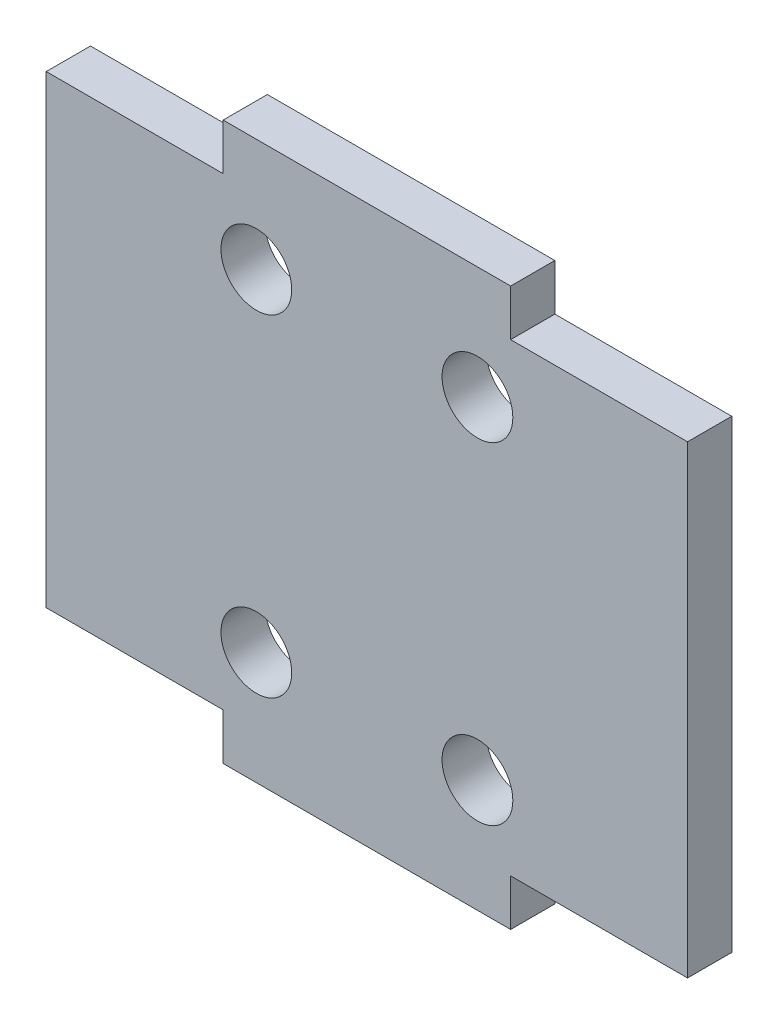
SolidWorks part; units mm, degrees
ref_plane "前视基准面" through (0, 0, 0) normal (0, 0, 1) x (1, 0, 0)
ref_plane "上视基准面" through (0, 0, 0) normal (0, 1, 0) x (1, 0, 0)
ref_plane "右视基准面" through (0, 0, 0) normal (1, 0, 0) x (0, 0, -1)
other "Configuration Table"
sketch "草图1" plane through (0, 0, 0) normal (0, 0, 1) x (1, 0, 0)
  line L0 (0, 0) -> (29, 0)
  line L1 (29, 0) -> (29, 21)
  line L2 (29, 21) -> (0, 21)
  line L3 (0, 21) -> (0, 0)
  line L4 (-8.8099, 10.5) -> (57.9745, 10.5) construction
  line L5 (14.5, 26.0654) -> (14.5, -5.792) construction
  line L6 (8, 0) -> (8, -2.1)
  line L7 (8, -2.1) -> (21, -2.1)
  line L8 (21, 0) -> (21, -2.1)
  line L9 (14.5, -5.0654) -> (14.5, 26.792) construction
  line L10 (21, 21) -> (21, 23.1)
  line L11 (8, 23.1) -> (21, 23.1)
  line L12 (8, 21) -> (8, 23.1)
  circle A0 centre (19.5, 18) radius 1.6
  circle A1 centre (9.5, 18) radius 1.6
  circle A2 centre (9.5, 3) radius 1.6
  circle A3 centre (19.5, 3) radius 1.6
  point P15 (14.5, -2.1)
  point P22 (14.5, 23.1)
  dimension "D3" = 3.2
  dimension "D1" = 21
  dimension "D2" = 29
  dimension "D4" = 10
  dimension "D5" = 15
  dimension "D6" = 13
  dimension "D7" = 2.1
extrude "凸台-拉伸1" add sketch "草图1" along normal blind 2 contours L2 L3 L0 L1 A1 A0 A2 A3 | L8 L0 L6 L7 | L12 L2 L10 L11
